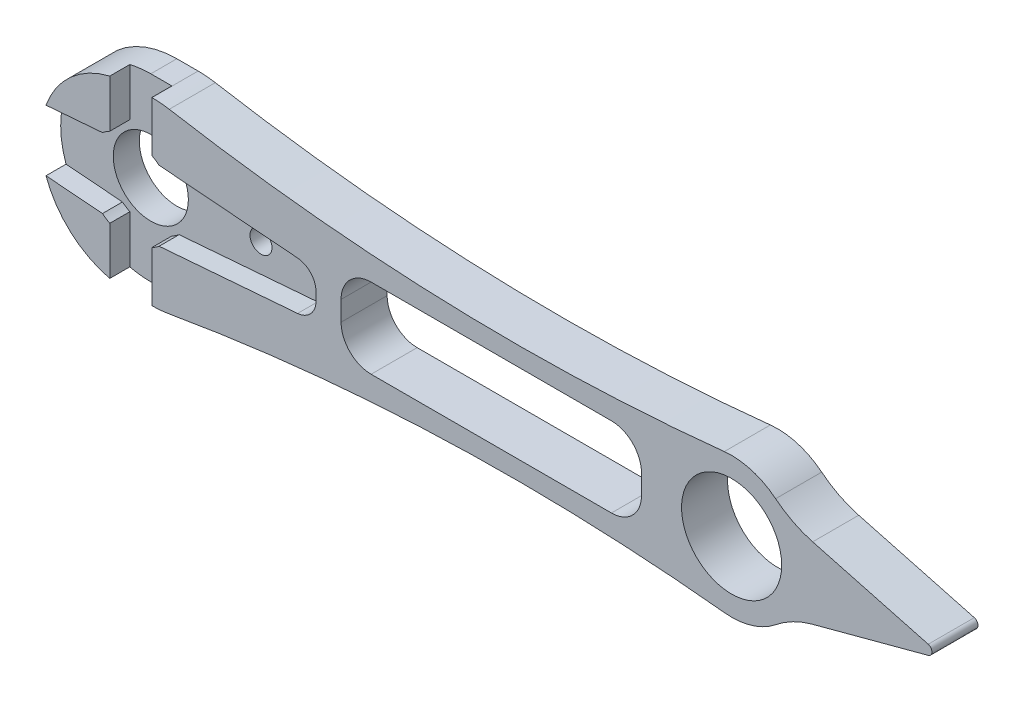
SolidWorks part; units mm, degrees
material "Epoxy, renforcé"
ref_plane "Plan de face" through (0, 0, 0) normal (0, 0, 1) x (1, 0, 0)
ref_plane "Plan de dessus" through (0, 0, 0) normal (0, 1, 0) x (1, 0, 0)
ref_plane "Plan de droite" through (0, 0, 0) normal (1, 0, 0) x (0, 0, -1)
sketch "Esquisse1" plane through (0, 0, 0) normal (0, 0, 1) x (1, 0, 0)
  line L0 (-30, 0) -> (30, 0) construction
  line L1 (-30, 9) -> (30, 9)
  line L2 (-30, -9) -> (30, -9)
  line L3 (0, 0) -> (0, 9) construction
  arc A0 (-30, 9) -> (-30, -9) centre (-30, 0) ccw
  arc A1 (30, -9) -> (30, 9) centre (30, 0) ccw
  circle A2 centre (-30, 0) radius 3.75
  circle A3 centre (30, 0) radius 1.6
  circle A4 centre (-19, 0) radius 1.1
  circle A5 centre (19, 0) radius 1.1 construction
  point P2 (0, 0)
  dimension "D1" = 7.5
  dimension "D4" = 2.2
  dimension "D5" = 3.2
  dimension "D2" = 18
  dimension "D3" = 60
  dimension "D6" = 11
extrude "Boss.-Extru.1" add sketch "Esquisse1" along normal blind 2.6
sketch "Esquisse2" plane through (0, 0, 2.6) normal (0, 0, 1) x (1, 0, 0)
  line L2 (-30, -9) -> (30, -9)
  line L3 (30, 9) -> (-30, 9)
  line L4 (-30, -9) -> (30, -9)
  line L5 (30, 9) -> (-30, 9)
  circle A0 centre (-30, 0) radius 3.75 construction
  circle A1 centre (-30, 0) radius 3.75
  arc A2 (-30, 9) -> (-30, -9) centre (-30, 0) ccw
  arc A3 (30, -9) -> (30, 9) centre (30, 0) ccw
  arc A4 (-30, 9) -> (-30, -9) centre (-30, 0) ccw
  arc A5 (30, -9) -> (30, 9) centre (30, 0) ccw
  circle A6 centre (30, 0) radius 1.6 construction
  circle A7 centre (30, 0) radius 1.6
  circle A8 centre (-19, 0) radius 1.1 construction
  circle A9 centre (-19, 0) radius 1.1
  dimension "D1" = 0
extrude "Boss.-Extru.2" add sketch "Esquisse2" along normal blind 2
sketch "Esquisse3" plane through (0, 0, 4.6) normal (0, 0, 1) x (1, 0, 0)
  line L0 (-21, 0) -> (-39, 0) construction
  line L1 (-30, 0) -> (-30, 9) construction
  line L2 (-32.1, 3.9799) -> (-32.1, 11)
  line L3 (-32.1, 11) -> (-27.9, 11)
  line L4 (-27.9, 11) -> (-27.9, 3.9799)
  line L5 (-27.9, -11) -> (-27.9, -3.9799)
  line L6 (-32.1, -11) -> (-27.9, -11)
  line L7 (-32.1, -3.9799) -> (-32.1, -11)
  line L8 (-32.8284, 3.5) -> (-48.5, 2.25)
  line L9 (-48.5, 2.25) -> (-48.5, -2.25)
  line L10 (-48.5, -2.25) -> (-32.8284, -3.5)
  line L11 (-11.5, -2.25) -> (-27.1716, -3.5)
  line L12 (-11.5, 2.25) -> (-11.5, -2.25)
  line L13 (-27.1716, 3.5) -> (-11.5, 2.25)
  line L14 (0, 0) -> (0, 9) construction
  line L15 (30, 9) -> (-30, 9) construction
  arc A0 (-32.8284, -3.5) -> (-32.1, -3.9799) centre (-30, 0) ccw
  arc A1 (-30, 9) -> (-30, -9) centre (-30, 0) ccw construction
  arc A2 (-32.1, 3.9799) -> (-32.8284, 3.5) centre (-30, 0) ccw
  arc A3 (-27.9, -3.9799) -> (-27.1716, -3.5) centre (-30, 0) ccw
  arc A4 (-27.1716, 3.5) -> (-27.9, 3.9799) centre (-30, 0) ccw
  dimension "D1" = 4.2
  dimension "D7" = 9
  dimension "D2" = 4.2
  dimension "D3" = 11
  dimension "D4" = 7
  dimension "D5" = 18.5
  dimension "D6" = 4.5
extrude "Enlèv. mat.-Extru.1" cut sketch "Esquisse3" against normal blind 2
sketch "Esquisse4" plane through (0, 0, 4.6) normal (0, 0, 1) x (1, 0, 0)
  line L0 (30, 9) -> (-27.9, 9) construction
  line L1 (0, 0) -> (39, 0) construction
  line L2 (-27, 9) -> (-27, 15.2625)
  line L3 (-27, 15.2625) -> (45.4943, 15.2625)
  line L5 (45.4943, 15.2625) -> (45.4943, -15.2625)
  line L6 (-27, -15.2625) -> (45.4943, -15.2625)
  line L7 (-27, -9) -> (-27, -15.2625)
  arc A0 (-27, 9) -> (29.2707, 6.9619) centre (8.3362, 206.7928) ccw
  arc A1 (-38.4674, 3.0502) -> (-38.4674, -3.0502) centre (-30, 0) ccw construction
  arc A2 (29.2707, -6.9619) -> (29.2707, 6.9619) centre (30, 0) ccw
  arc A3 (-27, -9) -> (29.2707, -6.9619) centre (8.3362, -206.7928) cw
  arc A4 (30, -9) -> (30, 9) centre (30, 0) ccw construction
  point P8 (-39, 0)
  point P13 (1.0636, 6)
  point P20 (45.4943, 0)
  dimension "D4" = 14
  dimension "D1" = 12
  dimension "D3" = 3
extrude "Enlèv. mat.-Extru.2" cut sketch "Esquisse4" against normal through all
fillet "Congé1" radius 2 2 edges at (-11.5, -2.25, 3.6) (-11.5, 2.25, 3.6)
fillet "Congé2" radius 10 2 edges at (-27, -9, 2.3) (-27, 9, 2.3)
sketch "Esquisse5" plane through (0, 0, 0) normal (0, 0, -1) x (-1, 0, 0)
  line L1 (20, 6) -> (-20, 6) construction
  line L2 (20, 6) -> (20, -6) construction
  line L3 (20, -6) -> (-20, -6) construction
  line L4 (-20, 6) -> (-20, -6) construction
  line L5 (20, 6) -> (-20, -6) construction
  line L6 (20, -6) -> (-20, 6) construction
  circle A0 centre (-20, 6) radius 0.9
  circle A1 centre (-20, -6) radius 0.9
  circle A2 centre (20, 6) radius 0.9
  circle A3 centre (20, -6) radius 0.9
  point P0 (0, 0)
  dimension "D3" = 1.8
  dimension "D1" = 40
  dimension "D2" = 12
extrude "Enlèv. mat.-Extru.3" [suppressed] cut sketch "Esquisse5" against normal through all
sketch "Esquisse6" plane through (0, 0, 4.6) normal (0, 0, 1) x (1, 0, 0)
  line L0 (-30, 0) -> (30, 0) construction
  line L1 (21, 3.985) -> (-9, 3.985)
  line L2 (21, 3.985) -> (21, -3.985)
  line L3 (21, -3.985) -> (-9, -3.985)
  line L4 (-9, 3.985) -> (-9, -3.985)
  line L5 (21, 3.985) -> (-9, -3.985) construction
  line L6 (21, -3.985) -> (-9, 3.985) construction
  arc A0 (-26.1586, 8.8515) -> (29.2707, 6.9619) centre (8.3362, 206.7928) ccw construction
  circle A1 centre (-30, 0) radius 3.75 construction
  point P0 (6, 0)
  point P9 (1.4905, 5.985)
  dimension "D1" = 2
  dimension "D2" = 30
  dimension "D3" = 36
extrude "Enlèv. mat.-Extru.4" cut sketch "Esquisse6" against normal blind 10
fillet "Congé3" radius 3 4 edges at (21, -3.985, 2.3) (21, 3.985, 2.3) (-9, -3.985, 2.3) (-9, 3.985, 2.3)
sketch "Esquisse7" plane through (0, 0, 0) normal (0, 0, 1) x (1, 0, 0)
  circle A0 centre (30, 0) radius 1.6
  dimension "D1" = 3.2
extrude "Enlèv. mat.-Extru.6" [suppressed] cut sketch "Esquisse7" along normal blind 3.2
sketch "Esquisse8" plane through (0, 0, 4.6) normal (0, 0, 1) x (1, 0, 0)
  line L0 (37, 0) -> (51.4447, 0) construction
  line L1 (51.4447, 0) -> (35.5673, 4.2433)
  line L2 (35.5673, 4.2433) -> (35.5673, -4.2433)
  line L3 (51.4447, 0) -> (35.5673, -4.2433)
  arc A0 (29.2707, -6.9619) -> (29.2707, 6.9619) centre (30, 0) ccw construction
  point P10 (35.5673, 0)
extrude "Boss.-Extru.3" add sketch "Esquisse8" against normal blind 4.6
fillet "Congé4" radius 0.5 1 edges at (51.4447, 0, 2.3)
sketch "Esquisse9" plane through (0, 0, 4.6) normal (0, 0, 1) x (1, 0, 0)
  circle A0 centre (30, 0) radius 5
  arc A1 (35.5673, 4.2433) -> (29.2707, 6.9619) centre (30, 0) ccw construction
  dimension "D1" = 2
extrude "Enlèv. mat.-Extru.7" cut sketch "Esquisse9" against normal through all
fillet "Congé5" radius 10 2 edges at (35.5673, -4.2433, 2.3) (35.5673, 4.2433, 2.3)
